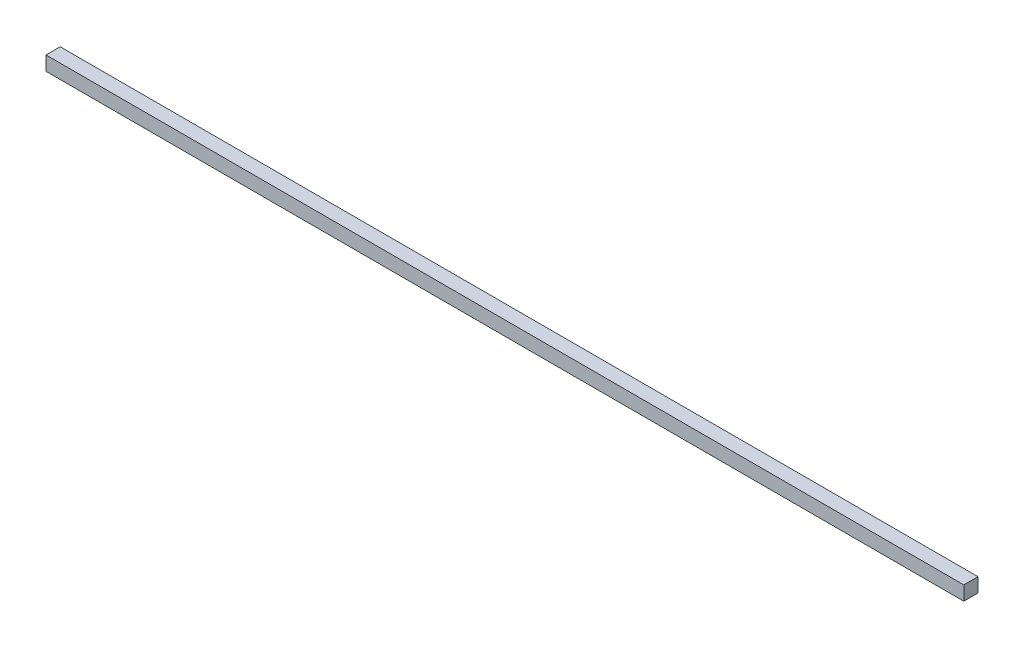
SolidWorks part; units mm, degrees
ref_plane "Front Plane" through (0, 0, 0) normal (0, 0, 1) x (1, 0, 0)
ref_plane "Top Plane" through (0, 0, 0) normal (0, 1, 0) x (1, 0, 0)
ref_plane "Right Plane" through (0, 0, 0) normal (1, 0, 0) x (0, 0, -1)
sketch "Sketch1" plane through (0, 0, 0) normal (1, 0, 0) x (0, 0, -1)
  line L1 (0, 0) -> (4.7625, 0)
  line L2 (0, 0) -> (0, 4.7625)
  line L3 (0, 4.7625) -> (4.7625, 4.7625)
  line L4 (4.7625, 0) -> (4.7625, 4.7625)
  dimension "D1" = 4.7625
extrude "Boss-Extrude1" add sketch "Sketch1" against normal blind 307.975 contours L1 L4 L3 L2
